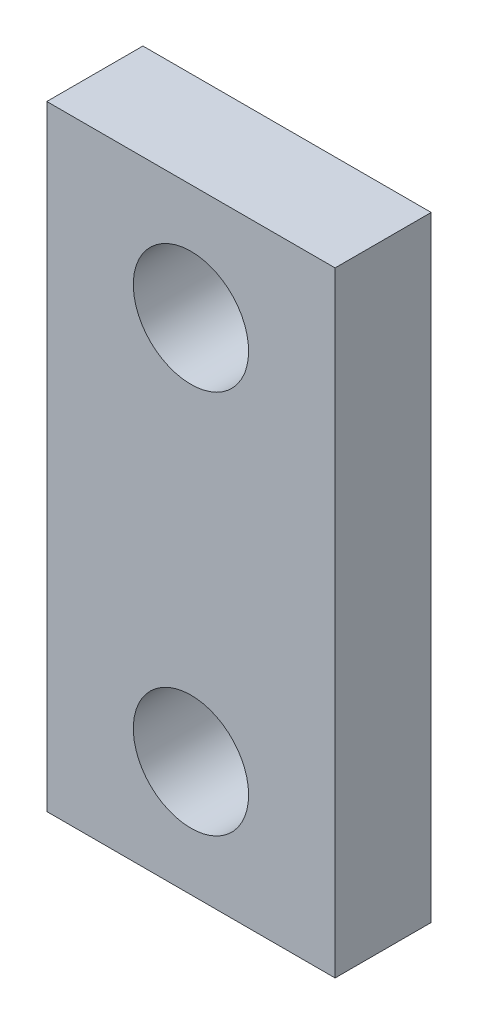
SolidWorks part; units mm, degrees
ref_plane "前视基准面" through (0, 0, 0) normal (0, 0, 1) x (1, 0, 0)
ref_plane "上视基准面" through (0, 0, 0) normal (0, 1, 0) x (1, 0, 0)
ref_plane "右视基准面" through (0, 0, 0) normal (1, 0, 0) x (0, 0, -1)
other "Configuration Table"
sketch "草图1" plane through (0, 0, 0) normal (0, 0, 1) x (1, 0, 0)
  line L0 (0, 23.8372) -> (0, -25) construction
  line L1 (-7.5, -16) -> (7.5, -16)
  line L2 (-7.5, -16) -> (-7.5, 16)
  line L3 (-7.5, 16) -> (7.5, 16)
  line L4 (7.5, -16) -> (7.5, 16)
  line L5 (-7.5, -16) -> (7.5, 16) construction
  line L6 (-7.5, 16) -> (7.5, -16) construction
  circle A0 centre (0, 10) radius 3
  circle A1 centre (0, -10) radius 3
  point P0 (0, 0)
  point P12 (0, 0)
  dimension "D3" = 6
  dimension "D4" = 6
  dimension "D1" = 32
  dimension "D2" = 15
  dimension "D5" = 20
  dimension "D6" = 6
extrude "凸台-拉伸1" add sketch "草图1" along normal blind 5
